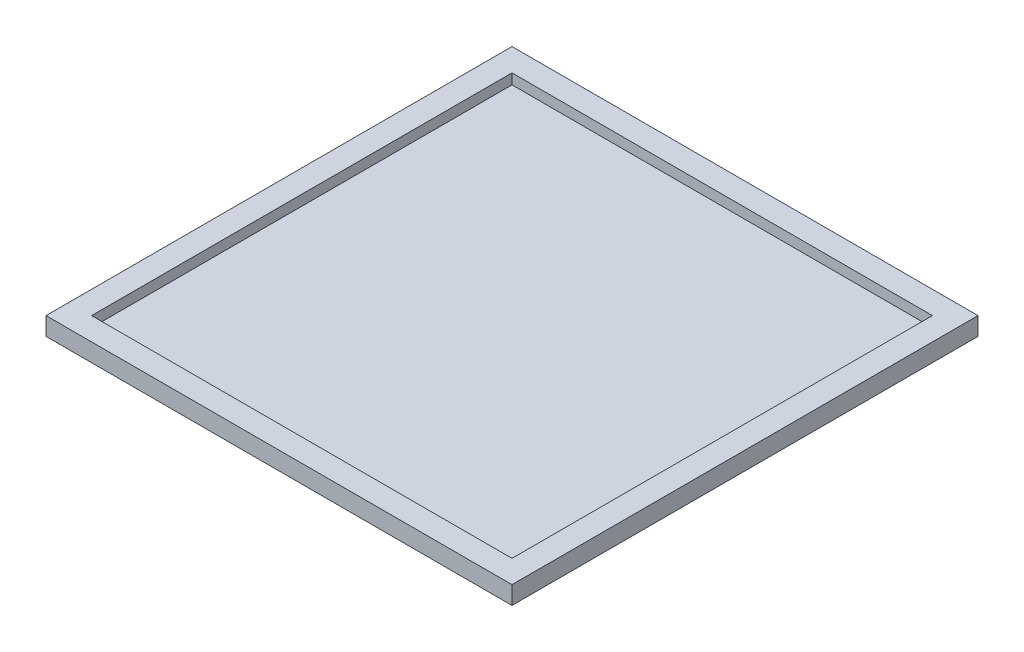
SolidWorks part; units mm, degrees
ref_plane "Front Plane" through (0, 0, 0) normal (0, 0, 1) x (1, 0, 0)
ref_plane "Top Plane" through (0, 0, 0) normal (0, 1, 0) x (1, 0, 0)
ref_plane "Right Plane" through (0, 0, 0) normal (1, 0, 0) x (0, 0, -1)
sketch "Sketch1" plane through (0, 0, 0) normal (0, 1, 0) x (1, 0, 0)
  line L1 (-325.6109, 372.0562) -> (494.3891, 372.0562)
  line L2 (-325.6109, 372.0562) -> (-325.6109, -447.9438)
  line L3 (-325.6109, -447.9438) -> (494.3891, -447.9438)
  line L4 (494.3891, 372.0562) -> (494.3891, -447.9438)
  dimension "D1" = 820
  dimension "D2" = 820
extrude "Boss-Extrude1" add sketch "Sketch1" along normal blind 31.7 contours L2 L1 L4 L3
sketch "Sketch2" plane through (0, 31.7, 0) normal (0, 1, 0) x (1, 0, 0)
  line L0 (-325.6109, 372.0562) -> (-325.6109, -447.9438) construction
  line L1 (-285.5109, 331.9562) -> (454.2891, 331.9562)
  line L2 (-285.5109, 331.9562) -> (-285.5109, -407.8438)
  line L3 (-285.5109, -407.8438) -> (454.2891, -407.8438)
  line L4 (454.2891, 331.9562) -> (454.2891, -407.8438)
  line L5 (494.3891, 372.0562) -> (494.3891, -447.9438) construction
  line L6 (-325.6109, 372.0562) -> (494.3891, 372.0562) construction
  line L7 (-325.6109, -447.9438) -> (494.3891, -447.9438) construction
  dimension "D1" = 40.1
  dimension "D2" = 40.1
  dimension "D3" = 40.1
  dimension "D4" = 40.1
extrude "Cut-Extrude1" cut sketch "Sketch2" against normal blind 18.31 contours L2 L1 L4 L3
